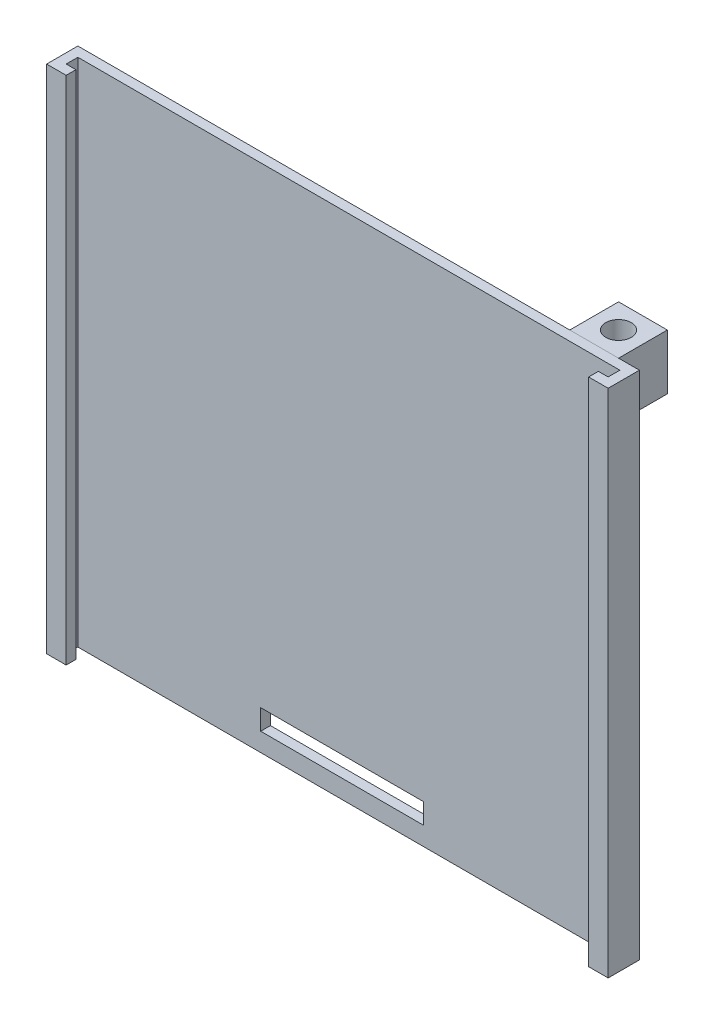
SolidWorks part; units mm, degrees
ref_plane "Front Plane" through (0, 0, 0) normal (0, 0, 1) x (1, 0, 0)
ref_plane "Top Plane" through (0, 0, 0) normal (0, 1, 0) x (1, 0, 0)
ref_plane "Right Plane" through (0, 0, 0) normal (1, 0, 0) x (0, 0, -1)
sketch "Sketch2" plane through (0, 0, 0) normal (0, 0, 1) x (1, 0, 0)
  line L5 (-105.791, -101.6) -> (105.791, -101.6)
  line L6 (-105.791, -101.6) -> (-105.791, 101.6)
  line L7 (-105.791, 101.6) -> (105.791, 101.6)
  line L8 (105.791, -101.6) -> (105.791, 101.6)
  line L9 (-105.791, -101.6) -> (105.791, 101.6) construction
  line L10 (-105.791, 101.6) -> (105.791, -101.6) construction
  point P0 (0, 0)
  dimension "D1" = 211.582
  dimension "D2" = 203.2
extrude "Boss-Extrude1" add sketch "Sketch2" along normal blind 3.81
sketch "Sketch4" plane through (-105.791, 0, 0) normal (-1, 0, 0) x (0, 0, 1)
  line L0 (0, 101.6) -> (0, -101.6) construction
  line L1 (0, 101.6) -> (12.192, 101.6)
  line L2 (0, 101.6) -> (0, -101.6)
  line L3 (0, -101.6) -> (12.192, -101.6)
  line L4 (12.192, 101.6) -> (12.192, -101.6)
  dimension "D1" = 12.192
extrude "Boss-Extrude2" add sketch "Sketch4" along normal blind 3.81
sketch "Sketch5" plane through (105.791, 0, 0) normal (1, 0, 0) x (0, 0, -1)
  line L1 (0, 101.6) -> (-12.192, 101.6)
  line L2 (0, 101.6) -> (0, -101.6)
  line L3 (0, -101.6) -> (-12.192, -101.6)
  line L4 (-12.192, 101.6) -> (-12.192, -101.6)
  dimension "D1" = 12.192
extrude "Boss-Extrude3" add sketch "Sketch5" along normal blind 3.81
sketch "Sketch6" plane through (105.791, 0, 0) normal (-1, 0, 0) x (0, 0, 1)
  line L0 (12.192, -101.6) -> (3.81, -101.6) construction
  line L1 (12.192, 101.6) -> (8.382, 101.6)
  line L2 (12.192, 101.6) -> (12.192, -101.6)
  line L3 (12.192, -101.6) -> (8.382, -101.6)
  line L4 (8.382, 101.6) -> (8.382, -101.6)
  dimension "D1" = 3.81
extrude "Boss-Extrude4" add sketch "Sketch6" along normal blind 3.81
sketch "Sketch7" plane through (-105.791, 0, 0) normal (1, 0, 0) x (0, 0, -1)
  line L5 (-3.81, -101.6) -> (-12.192, -101.6) construction
  line L6 (-12.192, 101.6) -> (-8.382, 101.6)
  line L7 (-12.192, 101.6) -> (-12.192, -101.6)
  line L8 (-12.192, -101.6) -> (-8.382, -101.6)
  line L9 (-8.382, 101.6) -> (-8.382, -101.6)
  dimension "D1" = 3.81
extrude "Boss-Extrude5" add sketch "Sketch7" along normal blind 3.81
sketch "Sketch9" plane through (0, 101.6, 0) normal (0, 1, 0) x (1, 0, 0)
  line L1 (-131.3261, 29.8908) -> (122.7859, 29.8908)
  line L2 (-131.3261, 29.8908) -> (-131.3261, -33.4358)
  line L3 (-131.3261, -33.4358) -> (122.7859, -33.4358)
  line L4 (122.7859, 29.8908) -> (122.7859, -33.4358)
extrude "Cut-Extrude1" cut sketch "Sketch9" against normal blind 3.81
sketch "Sketch10" plane through (0, 0, 0) normal (0, 0, -1) x (-1, 0, 0)
  line L0 (-109.601, 97.79) -> (-101.473, 97.79) construction
  line L1 (109.601, 97.79) -> (-109.601, 97.79) construction
  line L3 (-101.473, 97.79) -> (-82.423, 97.79)
  line L4 (-101.473, 97.79) -> (-101.473, 76.2)
  line L5 (-101.473, 76.2) -> (-82.423, 76.2)
  line L6 (-82.423, 97.79) -> (-82.423, 76.2)
  dimension "D1" = 8.128
  dimension "D2" = 19.05
  dimension "D3" = 21.59
extrude "Boss-Extrude6" add sketch "Sketch10" along normal blind 19.05 separate body
sketch "Sketch11" plane through (0, 97.79, 0) normal (0, 1, 0) x (1, 0, 0)
  line L0 (82.423, 19.05) -> (101.473, 0) construction
  line L1 (101.473, 19.05) -> (101.473, 0) construction
  circle A0 centre (91.948, 9.525) radius 5
  dimension "D1" = 10
extrude "Cut-Extrude2" cut sketch "Sketch11" against normal blind 21.59
sketch "Sketch13" plane through (0, 0, 0) normal (0, 0, -1) x (-1, 0, 0)
  line L0 (109.601, -101.5829) -> (34.417, -101.6) construction
  line L1 (109.601, 97.79) -> (109.601, -101.6) construction
  line L2 (109.601, -101.6) -> (-109.601, -101.6) construction
  line L3 (-109.601, -101.6) -> (-29.083, -101.6) construction
  line L4 (-109.601, -101.6) -> (-109.601, 97.79) construction
  line L5 (-29.083, -101.6) -> (-29.083, -96.52)
  line L7 (-29.083, -94.375) -> (34.417, -94.375)
  line L8 (-29.083, -94.375) -> (-29.083, -86.4083)
  line L9 (-29.083, -86.4083) -> (34.417, -86.4083)
  line L10 (34.417, -94.375) -> (34.417, -86.4083)
  dimension "D1" = 75.184
  dimension "D2" = 80.518
  dimension "D3" = 5.08
  dimension "D4" = 63.5
extrude "Cut-Extrude3" cut sketch "Sketch13" against normal blind 3.81 contours L8 L7 L10 L9
